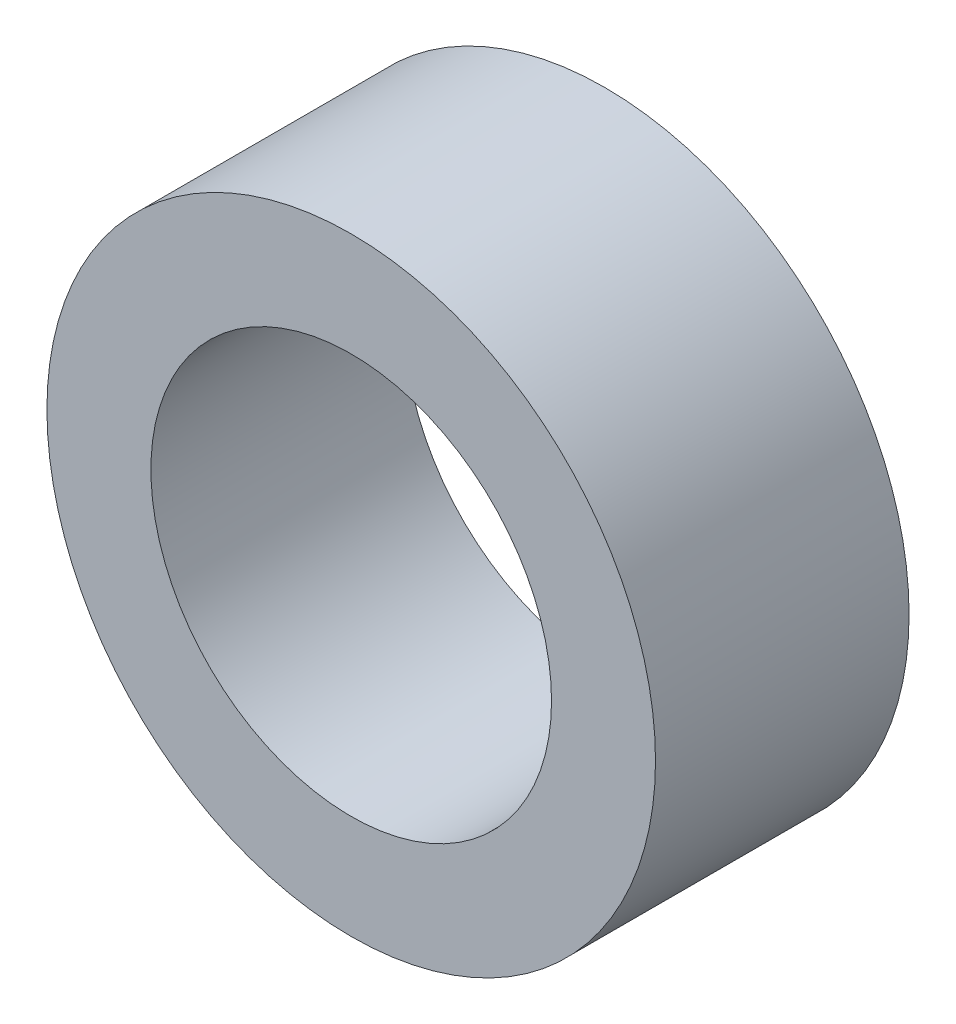
SolidWorks part; units mm, degrees
ref_plane "Front Plane" through (0, 0, 0) normal (0, 0, 1) x (1, 0, 0)
ref_plane "Top Plane" through (0, 0, 0) normal (0, 1, 0) x (1, 0, 0)
ref_plane "Right Plane" through (0, 0, 0) normal (1, 0, 0) x (0, 0, -1)
sketch "Sketch1" plane through (0, 0, 0) normal (0, 0, 1) x (1, 0, 0)
  circle A0 centre (0, 0) radius 6
  circle A1 centre (0, 0) radius 3.95
  dimension "D1" = 7.9
  dimension "D2" = 12
extrude "Boss-Extrude1" add sketch "Sketch1" along normal blind 5
